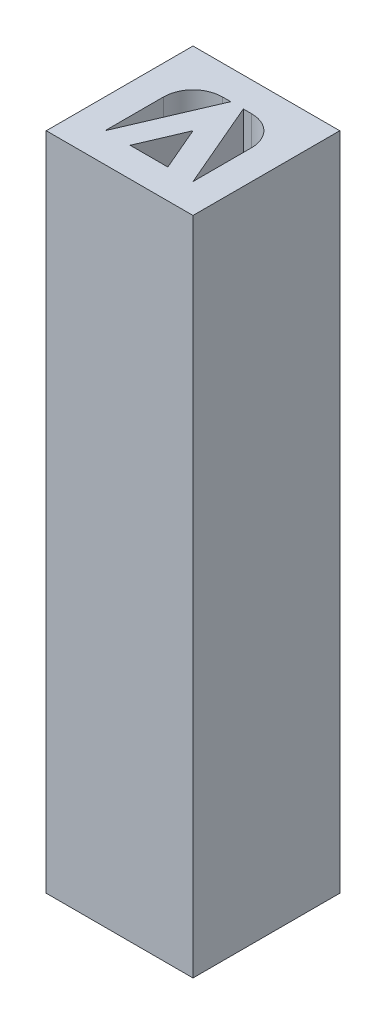
SolidWorks part; units mm, degrees
ref_plane "Front Plane" through (0, 0, 0) normal (0, 0, 1) x (1, 0, 0)
ref_plane "Top Plane" through (0, 0, 0) normal (0, 1, 0) x (1, 0, 0)
ref_plane "Right Plane" through (0, 0, 0) normal (1, 0, 0) x (0, 0, -1)
sketch "Sketch1" plane through (0, 0, 0) normal (0, 1, 0) x (1, 0, 0)
  line L0 (5, 10) -> (5, 8) construction
  line L1 (0, 0) -> (10, 0)
  line L2 (0, 0) -> (0, 10)
  line L3 (0, 10) -> (10, 10)
  line L4 (10, 0) -> (10, 10)
  line L5 (2, 8) -> (8, 8)
  line L6 (2, 8) -> (2, 2)
  line L7 (2, 2) -> (8, 2)
  line L8 (8, 8) -> (8, 2)
  line L9 (0, 5) -> (2, 5) construction
  dimension "D1" = 10
  dimension "D2" = 10
  dimension "D3" = 2
  dimension "D4" = 2
extrude "Boss-Extrude1" add sketch "Sketch1" along normal blind 45
sketch "Sketch3" plane through (0, 0, 0) normal (0, -1, 0) x (1, 0, 0)
  line L0 (8, -2) -> (5, -9)
  line L2 (5, -9) -> (2, -2)
  line L3 (5, -9) -> (5, -2) construction
  line L4 (2, -2) -> (8, -2) construction
  line L5 (8, -2) -> (6.2857, -2)
  line L6 (6.2857, -2) -> (5, -5)
  line L7 (5, -5) -> (3.7143, -2)
  line L8 (3.7143, -2) -> (2, -2)
  line L9 (8, -8) -> (2, -8) construction
  dimension "D1" = 4
  dimension "D2" = 1
extrude "Boss-Extrude4" add sketch "Sketch3" against normal through all
fillet "Fillet2" radius 2 2 edges at (2, 22.5, -8) (8, 22.5, -8)
